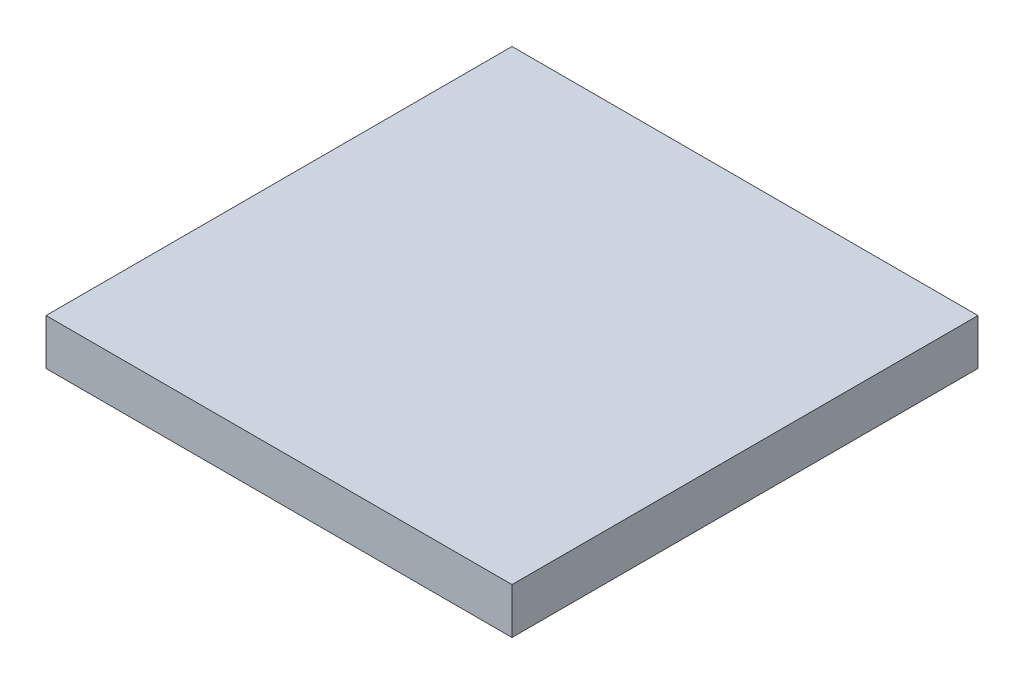
SolidWorks part; units mm, degrees
ref_plane "Front Plane" through (0, 0, 0) normal (0, 0, 1) x (1, 0, 0)
ref_plane "Top Plane" through (0, 0, 0) normal (0, 1, 0) x (1, 0, 0)
ref_plane "Right Plane" through (0, 0, 0) normal (1, 0, 0) x (0, 0, -1)
sketch "Sketch1" plane through (0, 0, 0) normal (0, 1, 0) x (1, 0, 0)
  line L1 (-50.8, -50.8) -> (50.8, -50.8)
  line L2 (-50.8, -50.8) -> (-50.8, 50.8)
  line L3 (-50.8, 50.8) -> (50.8, 50.8)
  line L4 (50.8, -50.8) -> (50.8, 50.8)
  line L5 (-50.8, -50.8) -> (50.8, 50.8) construction
  line L6 (-50.8, 50.8) -> (50.8, -50.8) construction
  point P0 (0, 0)
  dimension "D1" = 101.6
extrude "Boss-Extrude1" add sketch "Sketch1" along normal blind 10
sketch "Sketch2" plane through (0, 0, 0) normal (0, -1, 0) x (-1, 0, 0)
  circle A0 centre (0, 0) radius 3.175
  dimension "D1" = 6.35
extrude "Cut-Extrude1" cut sketch "Sketch2" against normal blind 5
